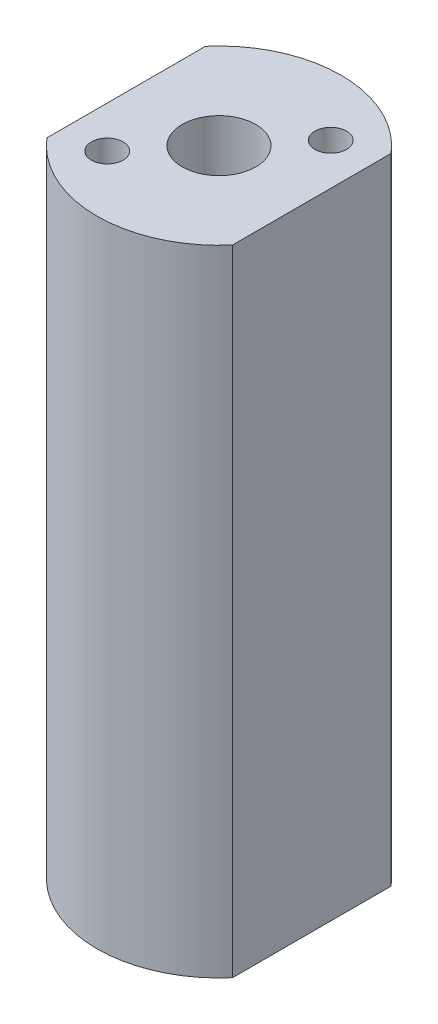
SolidWorks part; units mm, degrees
ref_plane "Front Plane" through (0, 0, 0) normal (0, 0, 1) x (1, 0, 0)
ref_plane "Top Plane" through (0, 0, 0) normal (0, 1, 0) x (1, 0, 0)
ref_plane "Right Plane" through (0, 0, 0) normal (1, 0, 0) x (0, 0, -1)
sketch "Sketch1" plane through (0, 0, 0) normal (0, 1, 0) x (1, 0, 0)
  line L1 (-5.85, 4.9991) -> (-5.85, -4.9991)
  line L2 (5.85, 4.9991) -> (5.85, -4.9991)
  arc A0 (5.85, 4.9991) -> (-5.85, 4.9991) centre (0, 0) ccw
  arc A1 (-5.85, -4.9991) -> (5.85, -4.9991) centre (0, 0) ccw
  dimension "D1" = 15.39
extrude "Boss-Extrude1" add sketch "Sketch1" along normal blind 40
sketch "Sketch2" plane through (0, 40, 0) normal (0, 1, 0) x (1, 0, 0)
  circle A0 centre (0, 0) radius 2.32
  circle A1 centre (3.2307, 3.8161) radius 1
  circle A2 centre (-3.2307, -3.8161) radius 1
  dimension "D1" = 4.64
  dimension "D2" = 2
  dimension "D3" = 2
  dimension "D4" = 5
  dimension "D5" = 5
extrude "Cut-Extrude1" cut sketch "Sketch2" against normal blind 40
